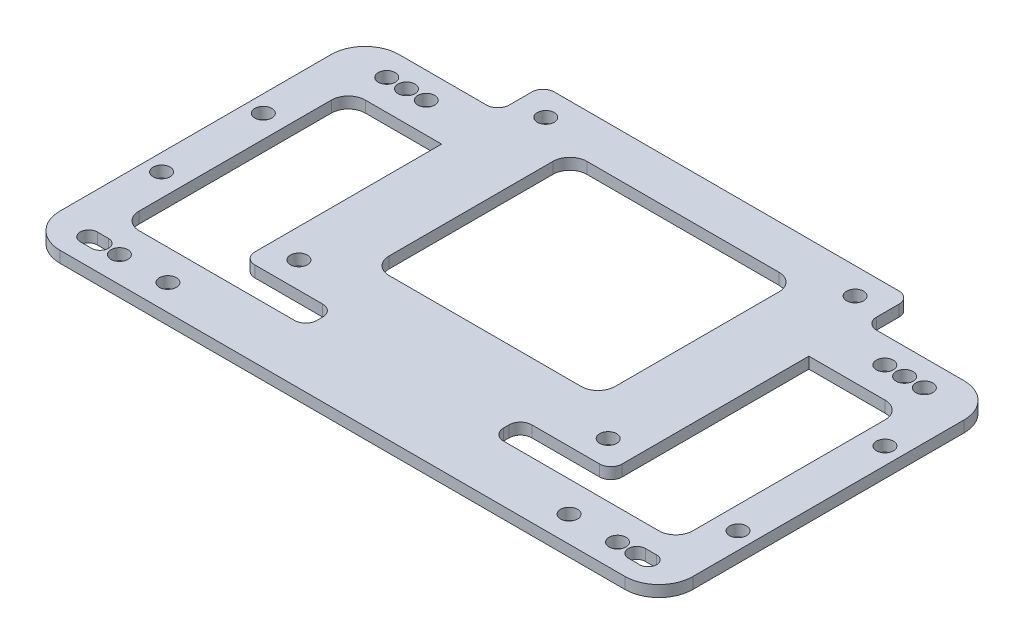
SolidWorks part; units mm, degrees
material "Thornel Mat VMA"
ref_plane "前视基准面" through (0, 0, 0) normal (0, 0, 1) x (1, 0, 0)
ref_plane "上视基准面" through (0, 0, 0) normal (0, 1, 0) x (1, 0, 0)
ref_plane "右视基准面" through (0, 0, 0) normal (1, 0, 0) x (0, 0, -1)
other "Configuration Table"
sketch "草图1" plane through (0, 0, 0) normal (0, 1, 0) x (1, 0, 0)
  line L1 (-49.9904, -29.947) -> (49.9904, -29.947)
  line L2 (-56, -23.9373) -> (-56, 24.0434)
  line L3 (-49.9904, 30.053) -> (-34.4974, 30.053)
  line L4 (56, -23.9373) -> (56, 24.0434)
  line L7 (-46, -19.9495) -> (-18.5, -19.9495)
  line L8 (-49, -16.9495) -> (-49, 17.0898)
  line L9 (-46, 20.0898) -> (-32.5, 20.0898)
  line L10 (49, -16.9495) -> (49, 17.0898)
  line L13 (-30.5, 38.0505) -> (30.5, 38.0505)
  line L14 (-32.5, 36.0505) -> (-32.5, 32.0505)
  line L15 (-30.5, -14.9495) -> (-18.5, -14.9495)
  line L16 (32.5, 36.0505) -> (32.5, 32.0505)
  line L23 (-17, 30.3005) -> (17, 30.3005)
  line L24 (-20, 27.3005) -> (-20, -1.6995)
  line L25 (-17, -4.6995) -> (17, -4.6995)
  line L26 (20, 27.3005) -> (20, -1.6995)
  line L38 (34.4974, 30.053) -> (49.9904, 30.053)
  line L40 (47.5, -25.347) -> (49.5, -25.347) construction
  line L41 (47.5, -23.847) -> (49.5, -23.847)
  line L44 (-32.5, 20.0898) -> (-32.5, -12.9495)
  line L46 (32.5, 20.0898) -> (46, 20.0898)
  line L47 (32.5, 20.0898) -> (32.5, -12.9495)
  line L48 (47.5, -26.847) -> (49.5, -26.847)
  line L51 (16.5, -17.9495) -> (16.5, -16.9495)
  line L52 (-16.5, -17.9495) -> (-16.5, -16.9495)
  line L53 (18.5, -19.9495) -> (46, -19.9495)
  line L54 (18.5, -14.9495) -> (30.5, -14.9495)
  line L55 (-47.5, -25.347) -> (-49.5, -25.347) construction
  line L56 (-47.5, -23.8399) -> (-49.5, -23.8399)
  line L57 (-47.5, -26.854) -> (-49.5, -26.854)
  circle A0 centre (27.37, 33.3955) radius 1.5
  circle A1 centre (27.37, -10.2945) radius 1.5
  arc A2 (30.5, -14.9495) -> (32.5, -12.9495) centre (30.5, -12.9495) ccw
  arc A3 (-32.5, -12.9495) -> (-30.5, -14.9495) centre (-30.5, -12.9495) ccw
  arc A4 (30.5, 38.0505) -> (32.5, 36.0505) centre (30.5, 36.0505) cw
  arc A5 (-30.5, 38.0505) -> (-32.5, 36.0505) centre (-30.5, 36.0505) ccw
  arc A6 (-17, 30.3005) -> (-20, 27.3005) centre (-17, 27.3005) ccw
  arc A7 (-20, -1.6995) -> (-17, -4.6995) centre (-17, -1.6995) ccw
  arc A8 (17, -4.6995) -> (20, -1.6995) centre (17, -1.6995) ccw
  arc A9 (17, 30.3005) -> (20, 27.3005) centre (17, 27.3005) cw
  arc A10 (49.9904, -29.947) -> (56, -23.9373) centre (49.9904, -23.9373) ccw
  arc A11 (-49.9904, -29.947) -> (-56, -23.9373) centre (-49.9904, -23.9373) cw
  arc A12 (-56, 24.0434) -> (-49.9904, 30.053) centre (-49.9904, 24.0434) cw
  arc A13 (49.9904, 30.053) -> (56, 24.0434) centre (49.9904, 24.0434) cw
  arc A14 (-46, -19.9495) -> (-49, -16.9495) centre (-46, -16.9495) cw
  arc A15 (-49, 17.0898) -> (-46, 20.0898) centre (-46, 17.0898) cw
  arc A16 (46, -19.9495) -> (49, -16.9495) centre (46, -16.9495) ccw
  arc A17 (46, 20.0898) -> (49, 17.0898) centre (46, 17.0898) cw
  arc A18 (34.4974, 30.053) -> (32.5, 32.0505) centre (34.4974, 32.0505) cw
  arc A19 (-34.4974, 30.053) -> (-32.5, 32.0505) centre (-34.4974, 32.0505) ccw
  arc A22 (47.5, -23.847) -> (47.5, -26.847) centre (47.5, -25.347) ccw
  arc A23 (49.5, -26.847) -> (49.5, -23.847) centre (49.5, -25.347) ccw
  circle A24 centre (53, 13.0505) radius 1.5
  circle A25 centre (53, -12.9495) radius 1.5
  arc A26 (16.5, -16.9495) -> (18.5, -14.9495) centre (18.5, -16.9495) cw
  arc A27 (18.5, -19.9495) -> (16.5, -17.9495) centre (18.5, -17.9495) cw
  arc A28 (-16.5, -17.9495) -> (-18.5, -19.9495) centre (-18.5, -17.9495) cw
  arc A29 (-16.5, -16.9495) -> (-18.5, -14.9495) centre (-18.5, -16.9495) ccw
  circle A30 centre (35.5, -25.347) radius 1.5
  arc A31 (-47.5, -23.8399) -> (-47.5, -26.854) centre (-47.5, -25.347) cw
  arc A32 (-49.5, -26.854) -> (-49.5, -23.8399) centre (-49.5, -25.347) cw
  circle A35 centre (-27.37, 33.3955) radius 1.5
  circle A36 centre (-53, 9.0505) radius 1.5
  circle A37 centre (-53, -8.9495) radius 1.5
  circle A38 centre (-35.5, -25.347) radius 1.5
  circle A39 centre (-27.37, -10.2945) radius 1.5
  circle A40 centre (-44.07, -25.347) radius 1.5
  circle A41 centre (44.07, -25.347) radius 1.5
  circle A42 centre (-44.07, 25.453) radius 1.5
  circle A43 centre (-47.57, 25.453) radius 1.5
  circle A44 centre (-40.57, 25.453) radius 1.5
  circle A45 centre (44.07, 25.453) radius 1.5
  circle A46 centre (47.57, 25.453) radius 1.5
  circle A47 centre (40.57, 25.453) radius 1.5
  point P0 (0, 0)
  point P6 (0, 0)
  point P11 (0, 11.5)
  point P24 (0, 12.8005)
  point P100 (48.5, -25.347)
  point P105 (27.37, 34.0505)
  point P108 (27.25, 34.0505)
  point P129 (-48.5, -25.347)
  dimension "D28" = 0
  dimension "D33" = 0
  dimension "D38" = 0
extrude "凸台-拉伸1" add sketch "草图1" along normal blind 2
